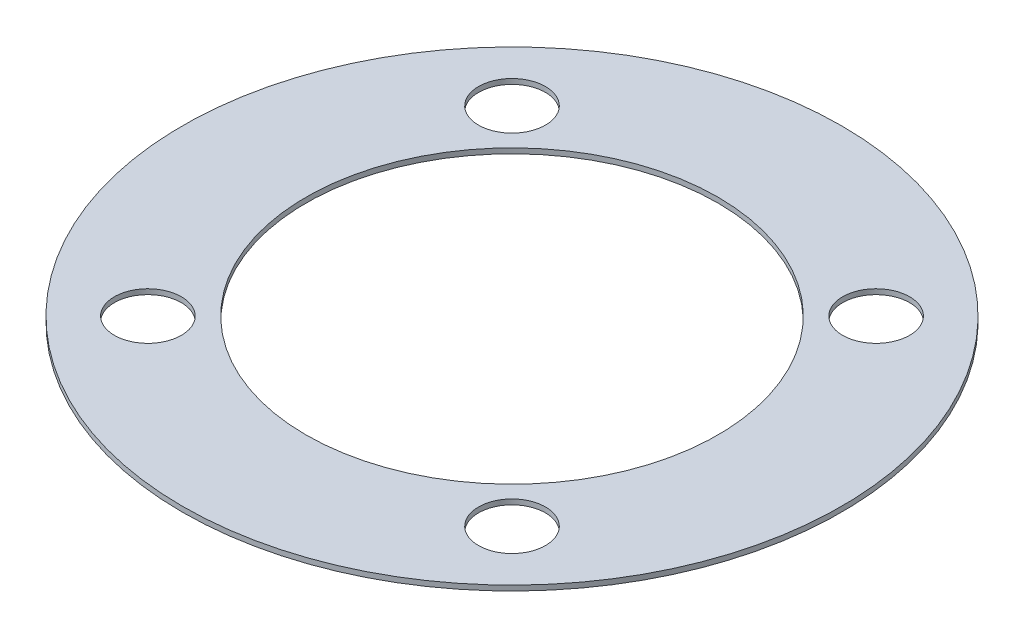
SolidWorks part; units mm, degrees
ref_plane "Front Plane" through (0, 0, 0) normal (0, 0, 1) x (1, 0, 0)
ref_plane "Top Plane" through (0, 0, 0) normal (0, 1, 0) x (1, 0, 0)
ref_plane "Right Plane" through (0, 0, 0) normal (1, 0, 0) x (0, 0, -1)
sketch "Sketch1" plane through (0, 0, 0) normal (0, 1, 0) x (1, 0, 0)
  line L0 (-17.6777, 17.6777) -> (0, 0) construction
  line L1 (0, 0) -> (0, 44.9419) construction
  circle A0 centre (0, 0) radius 20
  circle A1 centre (0, 0) radius 32
  circle A2 centre (0, 0) radius 25 construction
  circle A3 centre (-17.6777, 17.6777) radius 3.25
  circle A4 centre (17.6777, 17.6777) radius 3.25
  circle A5 centre (17.6777, -17.6777) radius 3.25
  circle A6 centre (-17.6777, -17.6777) radius 3.25
  point P7 (-29.2122, -25.5154)
  point P9 (0, 0)
  point P17 (0, 0)
  dimension "D1" = 50
  dimension "D2" = 40
  dimension "D3" = 64
  dimension "D4" = 6.5
  dimension "D5" = 45
  dimension "D6" = 4
extrude "Boss-Extrude1" add sketch "Sketch1" along normal blind 0.5
